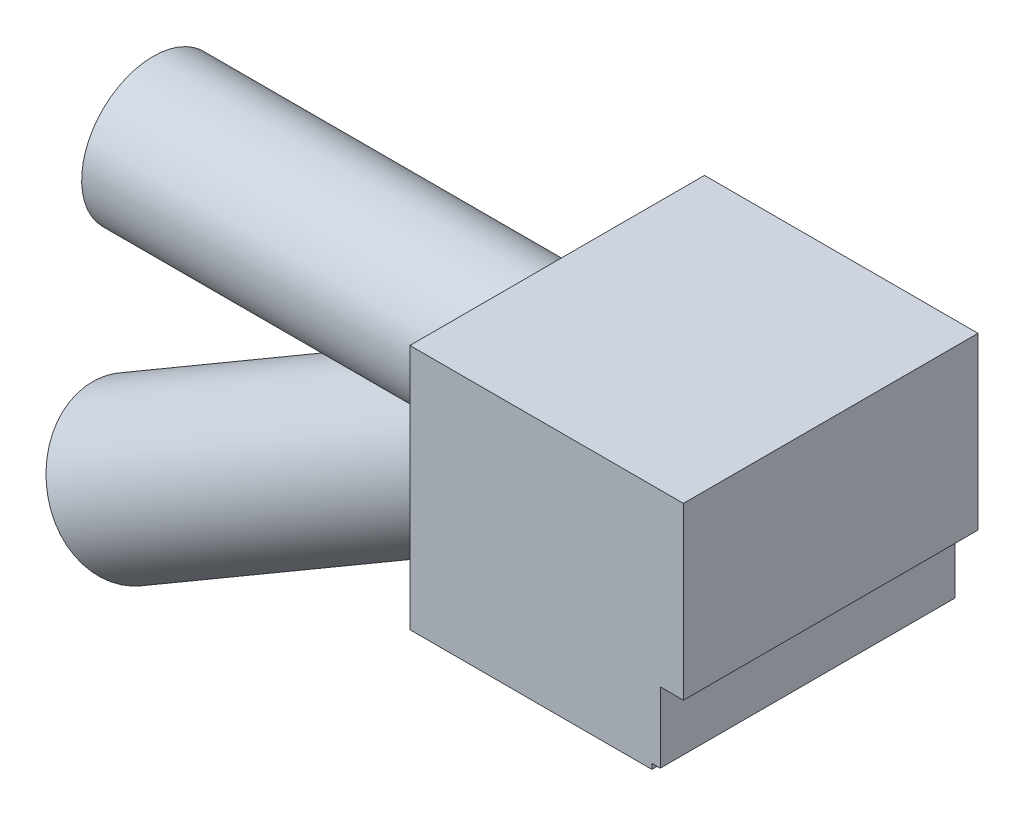
SolidWorks part; units mm, degrees
ref_plane "Plan de face" through (0, 0, 0) normal (0, 0, 1) x (1, 0, 0)
ref_plane "Plan de dessus" through (0, 0, 0) normal (0, 1, 0) x (1, 0, 0)
ref_plane "Plan de droite" through (0, 0, 0) normal (1, 0, 0) x (0, 0, -1)
sketch "Esquisse1" plane through (0, 0, 0) normal (1, 0, 0) x (0, 0, -1)
  circle A0 centre (0, 0) radius 17
  dimension "D1" = 34
extrude "Boss.-Extru.1" add sketch "Esquisse1" along normal blind 96
sketch "Esquisse2" plane through (96, 0, 0) normal (1, 0, 0) x (0, 0, -1)
  line L0 (-35, 23) -> (35, 23)
  line L1 (35, 23) -> (35, -35.5)
  line L2 (35, -35.5) -> (-35, -35.5)
  line L3 (-35, -35.5) -> (-35, 23)
  circle A0 centre (0, 0) radius 17
  point P7 (0, 23)
  point P8 (0, 0)
  point P9 (0, 0)
  dimension "D1" = 34
  dimension "D2" = 23
  dimension "D3" = 70
  dimension "D4" = 58.5
extrude "Boss.-Extru.3" add sketch "Esquisse2" along normal blind 65 contours L3 L0 L1 L2
sketch "Esquisse4" plane through (0, 0, 0) normal (0, 0, 1) x (1, 0, 0)
  line L0 (161, 0) -> (119, 0) construction
  line L1 (161, 23) -> (161, -35.5) construction
  line L2 (119, 0) -> (-5.3125, -72.6801) construction
  line L3 (-5.3125, -72.6801) -> (161, 0) construction
  line L4 (119, 0) -> (101.3985, 30.1057) construction
  dimension "D1" = 42
  dimension "D2" = 144
  dimension "D3" = 181.5
  dimension "D4" = 90
sketch3d "Esquisse3D2"
  line L0 (119, 0, 0) -> (101.3985, 30.1057, 0) construction
  line L1 (119, 0, 0) -> (-5.3125, -72.6801, 0) construction
sketch "Esquisse6" plane through (88.6853, 51.8504, 0) normal (0.8633, 0.5047, 0) x (0, 0, -1)
  line L0 (0, -60.0621) -> (0, -25.1884) construction
  circle A0 centre (0, -60.0621) radius 18
  dimension "D1" = 60.0621
  dimension "36" = 36
extrude "Boss.-Extru.4" add sketch "Esquisse6" against normal blind 144
sketch "Esquisse7" plane through (161, 0, 0) normal (1, 0, 0) x (0, 0, -1)
  line L1 (-35, -35.5) -> (-35, 23) construction
  line L2 (35, 23) -> (35, -35.5) construction
  line L5 (-35, -35.5) -> (35, -35.5)
  line L6 (-35, -35.5) -> (-35, -17.5)
  line L7 (-35, -17.5) -> (35, -17.5)
  line L8 (35, -35.5) -> (35, -17.5)
  dimension "D1" = 18
extrude "Enlèv. mat.-Extru.1" cut sketch "Esquisse7" against normal blind 5.5
sketch "Esquisse8" plane through (155.5, 0, 0) normal (1, 0, 0) x (0, 0, -1)
  line L0 (35, -35.5) -> (35, -17.5) construction
  line L1 (-35, -35.5) -> (35, -35.5)
  line L2 (-35, -35.5) -> (-35, -34.25)
  line L3 (-35, -34.25) -> (35, -34.25)
  line L4 (35, -35.5) -> (35, -34.25)
  dimension "D1" = 1.25
extrude "Enlèv. mat.-Extru.2" cut sketch "Esquisse8" against normal blind 2
sketch "Esquisse9" plane through (-35.6272, -20.8297, 0) normal (-0.8633, -0.5047, 0) x (0, 0, 1)
  line L0 (0, -60.0621) -> (-19.5, -60.0621) construction
  circle A0 centre (0, -60.0621) radius 18
  circle A2 centre (-19.5, -60.0621) radius 2.5
  dimension "D1" = 36
  dimension "D2" = 19.5
  dimension "D3" = 5
extrude "Boss.-Extru.5" add sketch "Esquisse9" against normal blind 120 contours A2
fillet "Congé1" radius 1 2 edges at (44.8595, -41.124, -17.8974) (45.828, -45.0032, -17.8974)
